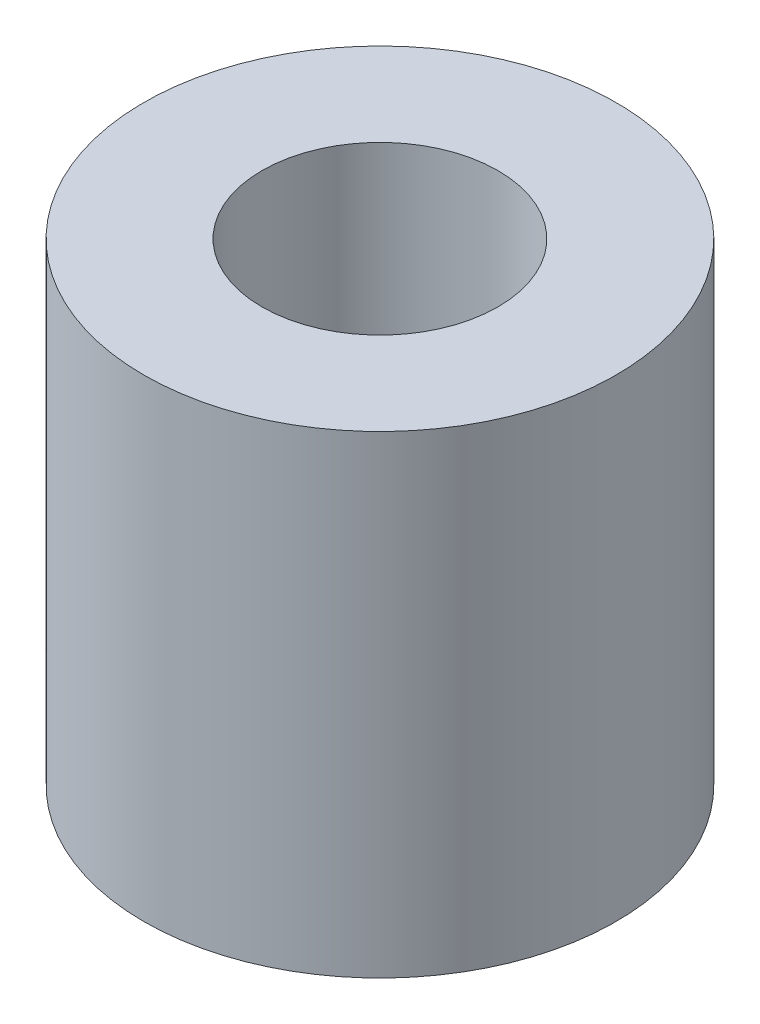
SolidWorks part; units mm, degrees
ref_plane "Plan de face" through (0, 0, 0) normal (0, 0, 1) x (1, 0, 0)
ref_plane "Plan de dessus" through (0, 0, 0) normal (0, 1, 0) x (1, 0, 0)
ref_plane "Plan de droite" through (0, 0, 0) normal (1, 0, 0) x (0, 0, -1)
sketch "Esquisse1" plane through (0, 0, 0) normal (0, 1, 0) x (1, 0, 0)
  circle A0 centre (0, 0) radius 2
  circle A1 centre (0, 0) radius 4
  dimension "D1" = 4
  dimension "D2" = 8
extrude "Boss.-Extru.1" add sketch "Esquisse1" along normal mid plane 8.0196
